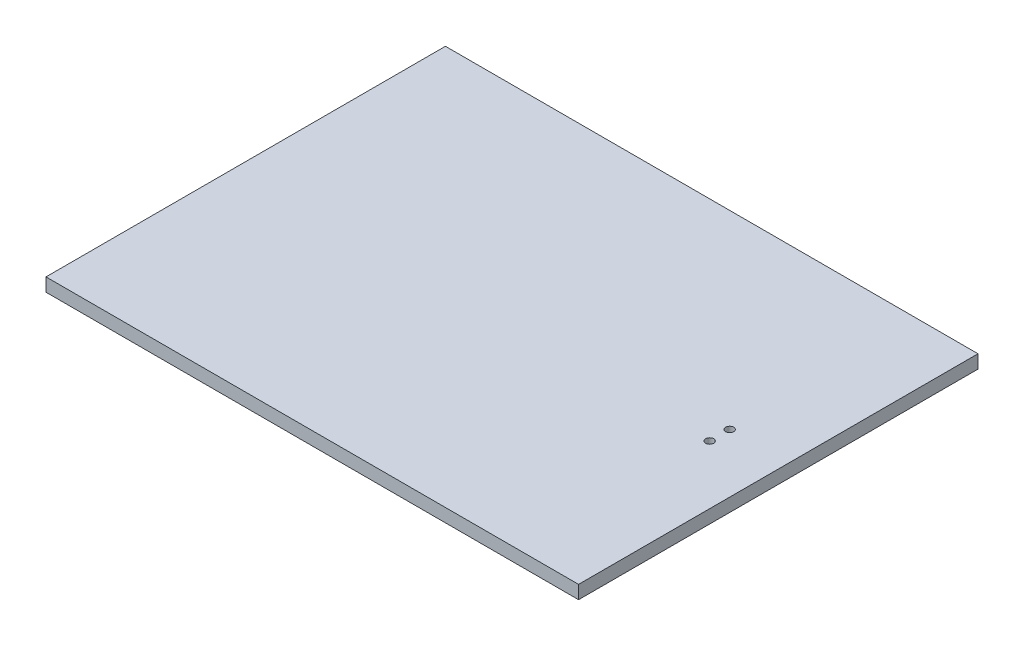
SolidWorks part; units mm, degrees
ref_plane "Front Plane" through (0, 0, 0) normal (0, 0, 1) x (1, 0, 0)
ref_plane "Top Plane" through (0, 0, 0) normal (0, 1, 0) x (1, 0, 0)
ref_plane "Right Plane" through (0, 0, 0) normal (1, 0, 0) x (0, 0, -1)
sketch "base_plate_sketch" plane through (0, 0, 0) normal (0, 1, 0) x (1, 0, 0)
  line L0 (-200, 0) -> (200, 0) construction
  line L1 (-200, 150) -> (200, 150)
  line L2 (-200, 150) -> (-200, -150)
  line L3 (-200, -150) -> (200, -150)
  line L4 (200, 150) -> (200, -150)
  circle A0 centre (156, 7.5) radius 3
  circle A1 centre (156, -7.5) radius 3
  point P4 (0, 150)
  point P6 (200, 0)
  dimension "D3" = 6
  dimension "D4" = 6
  dimension "D1" = 400
  dimension "D2" = 300
  dimension "D5" = 15
  dimension "D6" = 7.5
  dimension "D7" = 7.5
  dimension "D8" = 44
extrude "Boss-Extrude1" add sketch "base_plate_sketch" along normal blind 10
